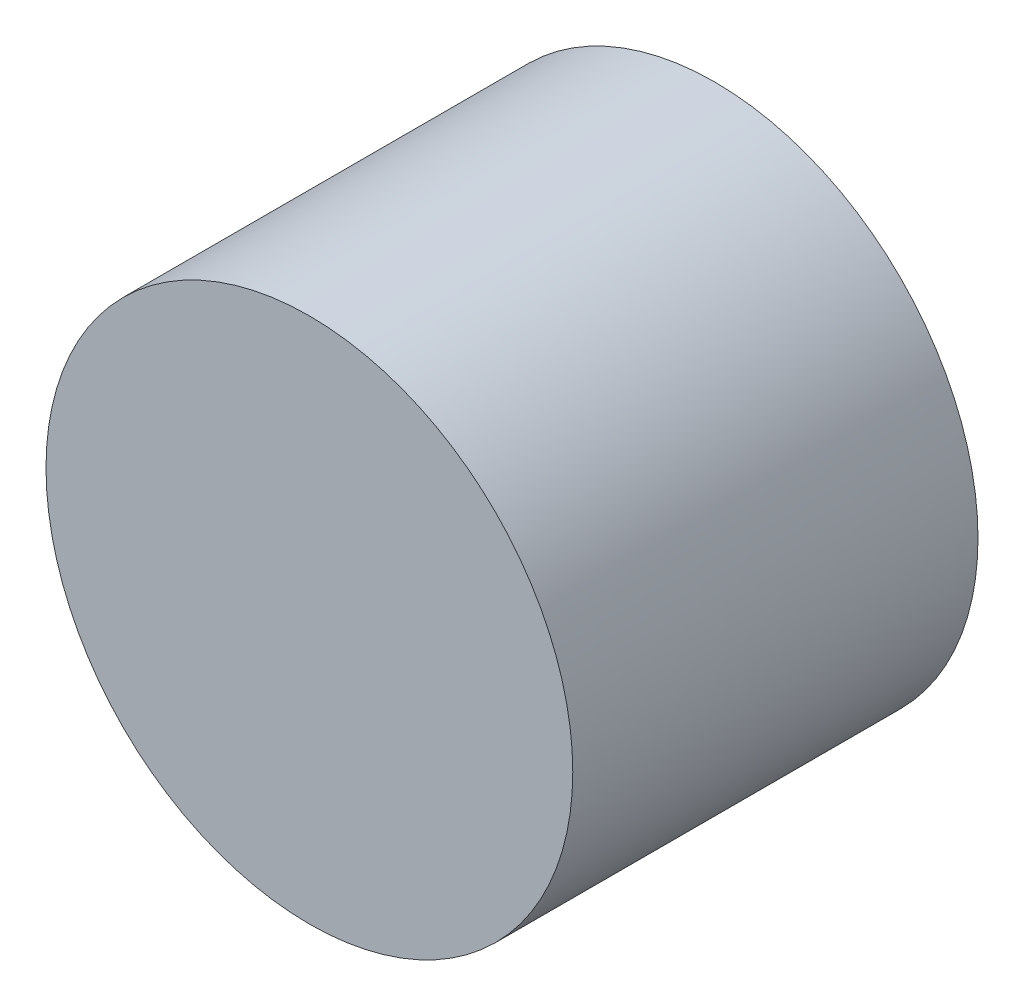
SolidWorks part; units mm, degrees
ref_plane "Спереди" through (0, 0, 0) normal (0, 0, 1) x (1, 0, 0)
ref_plane "Сверху" through (0, 0, 0) normal (0, 1, 0) x (1, 0, 0)
ref_plane "Справа" through (0, 0, 0) normal (1, 0, 0) x (0, 0, -1)
sketch "Эскиз1" plane through (0, 0, 0) normal (0, 0, 1) x (1, 0, 0)
  circle A0 centre (0, 0) radius 13
  dimension "D1" = 26
extrude "Бобышка-Вытянуть1" add sketch "Эскиз1" along normal blind 20
